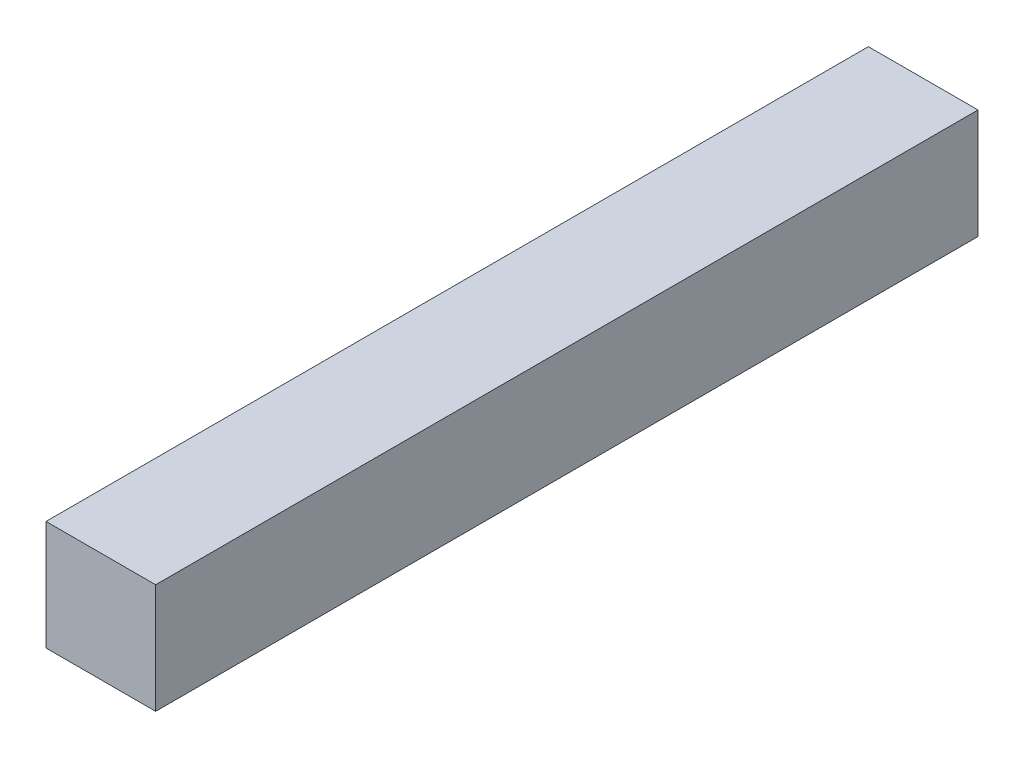
SolidWorks part; units mm, degrees
ref_plane "Front Plane" through (0, 0, 0) normal (0, 0, 1) x (1, 0, 0)
ref_plane "Top Plane" through (0, 0, 0) normal (0, 1, 0) x (1, 0, 0)
ref_plane "Right Plane" through (0, 0, 0) normal (1, 0, 0) x (0, 0, -1)
sketch "Sketch1" plane through (0, 0, 0) normal (0, 1, 0) x (1, 0, 0)
  line L1 (-16.9668, 13.2927) -> (23.0332, 13.2927)
  line L2 (-16.9668, 13.2927) -> (-16.9668, -286.7073)
  line L3 (-16.9668, -286.7073) -> (23.0332, -286.7073)
  line L4 (23.0332, 13.2927) -> (23.0332, -286.7073)
  dimension "D1" = 40
  dimension "D2" = 300
extrude "Boss-Extrude1" add sketch "Sketch1" along normal blind 40
equation "\"LegLength\"= 300"
equation "\"LegWidth\"= 40"
equation "\"LegHeight\"= 40"
equation "\"D1@Sketch1\"=\"LegWidth\""
equation "\"D2@Sketch1\"=\"LegLength\""
equation "\"D1@Boss-Extrude1\"=\"LegHeight\""
